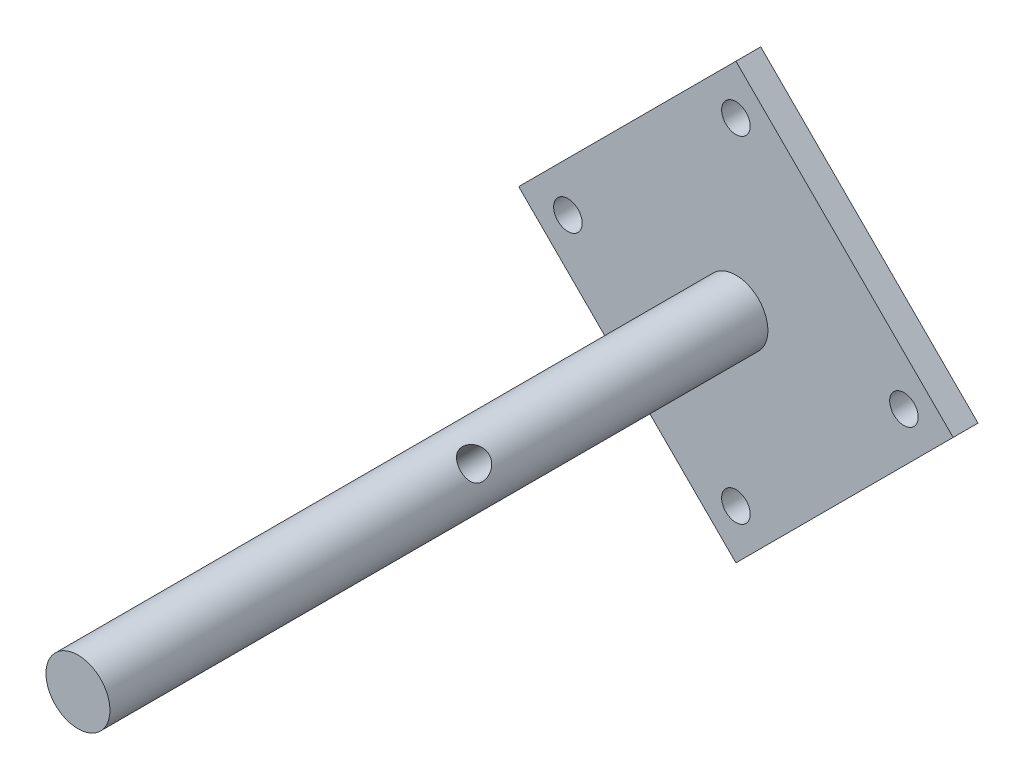
SolidWorks part; units mm, degrees
ref_plane "정면" through (0, 0, 0) normal (0, 0, 1) x (1, 0, 0)
ref_plane "윗면" through (0, 0, 0) normal (0, 1, 0) x (1, 0, 0)
ref_plane "우측면" through (0, 0, 0) normal (1, 0, 0) x (0, 0, -1)
sketch "스케치1" plane through (0, 0, 0) normal (0, 0, 1) x (1, 0, 0)
  circle A0 centre (0, 0) radius 2.575
  dimension "D1" = 5.15
extrude "보스-돌출1" add sketch "스케치1" along normal blind 55
sketch "스케치2" plane through (0, 0, 0) normal (0, 0, -1) x (-1, 0, 0)
  line L1 (17.5, -17.5) -> (-17.5, -17.5)
  line L2 (17.5, -17.5) -> (17.5, 17.5)
  line L3 (17.5, 17.5) -> (-17.5, 17.5)
  line L4 (-17.5, -17.5) -> (-17.5, 17.5)
  line L5 (17.5, -17.5) -> (-17.5, 17.5) construction
  line L6 (17.5, 17.5) -> (-17.5, -17.5) construction
  point P0 (0, 0)
  dimension "D1" = 35
  dimension "D2" = 35
extrude "보스-돌출2" add sketch "스케치2" against normal blind 2
sketch "스케치3" plane through (0, 0, 2) normal (0, 0, 1) x (1, 0, 0)
  line L0 (0, 0) -> (0, 3.071) construction
  circle A0 centre (6.5, 0) radius 1.15
  circle A1 centre (0, -6.5) radius 1.15
  circle A2 centre (-6.5, 0) radius 1.15
  circle A3 centre (0, 6.5) radius 1.15
  point P14 (0, 0)
  point P16 (0, 0)
  dimension "D2" = 2.3
  dimension "D1" = 6.5
  dimension "D3" = 4
ref_plane "평면1" through (0, 0, 29) normal (0, 0, 1) x (1, 0, 0)
sketch "스케치5" plane through (17.5, 0, 0) normal (1, 0, 0) x (0, 0, -1)
  line L0 (-23.7, 0) -> (-23.7, 6.152) construction
  line L3 (0, 17.5) -> (0, -17.5) construction
  circle A0 centre (-24.85, 0) radius 1.15
  dimension "D2" = 2.3
  dimension "D1" = 23.7
sketch "스케치7" plane through (0, 0, 0) normal (0, 0, -1) x (-1, 0, 0)
  circle A0 centre (0, 0) radius 10
  dimension "D1" = 20
sketch "스케치8" plane through (0, 0, 0) normal (0, 0, -1) x (-1, 0, 0)
  circle A0 centre (13.5337, 0) radius 1.15
  circle A1 centre (0, -13.5337) radius 1.15
  circle A2 centre (-13.5337, 0) radius 1.15
  circle A3 centre (0, 13.5337) radius 1.15
  point P11 (0, 0)
  dimension "D1" = 2.3
  dimension "D2" = 4
extrude "컷-돌출5" cut sketch "스케치8" against normal blind 5
sketch "스케치10" plane through (0, 0, 2) normal (0, 0, 1) x (1, 0, 0)
  line L0 (-17.5, 0) -> (0, 17.5)
  line L1 (-17.5, -17.5) -> (-17.5, 17.5) construction
  line L2 (-17.5, 17.5) -> (17.5, 17.5) construction
  line L3 (0, 17.5) -> (17.5, 0)
  line L4 (17.5, 17.5) -> (17.5, -17.5) construction
  line L5 (17.5, 0) -> (0, -17.5)
  line L6 (17.5, -17.5) -> (-17.5, -17.5) construction
  line L7 (0, -17.5) -> (-17.5, 0)
extrude "컷-돌출6" cut sketch "스케치10" against normal blind 5 flip side to cut
sketch "스케치11" plane through (0, 0, 55) normal (0, 0, 1) x (1, 0, 0)
  line L0 (0, 0) -> (0, 10.6826) construction
ref_plane "평면3" through (8.75, 8.75, 0) normal (0.7071, 0.7071, 0) x (0.7071, -0.7071, 0)
sketch "스케치14" plane through (8.75, 8.75, 0) normal (0.7071, 0.7071, 0) x (0.7071, -0.7071, 0)
  line L1 (0, -23.7) -> (-4.2614, -23.7) construction
  line L2 (10, 0) -> (-10, 0) construction
  circle A0 centre (0, -24.85) radius 1.15
  dimension "D1" = 2.3
  dimension "D2" = 23.7
extrude "컷-돌출7" cut sketch "스케치14" against normal blind 20
